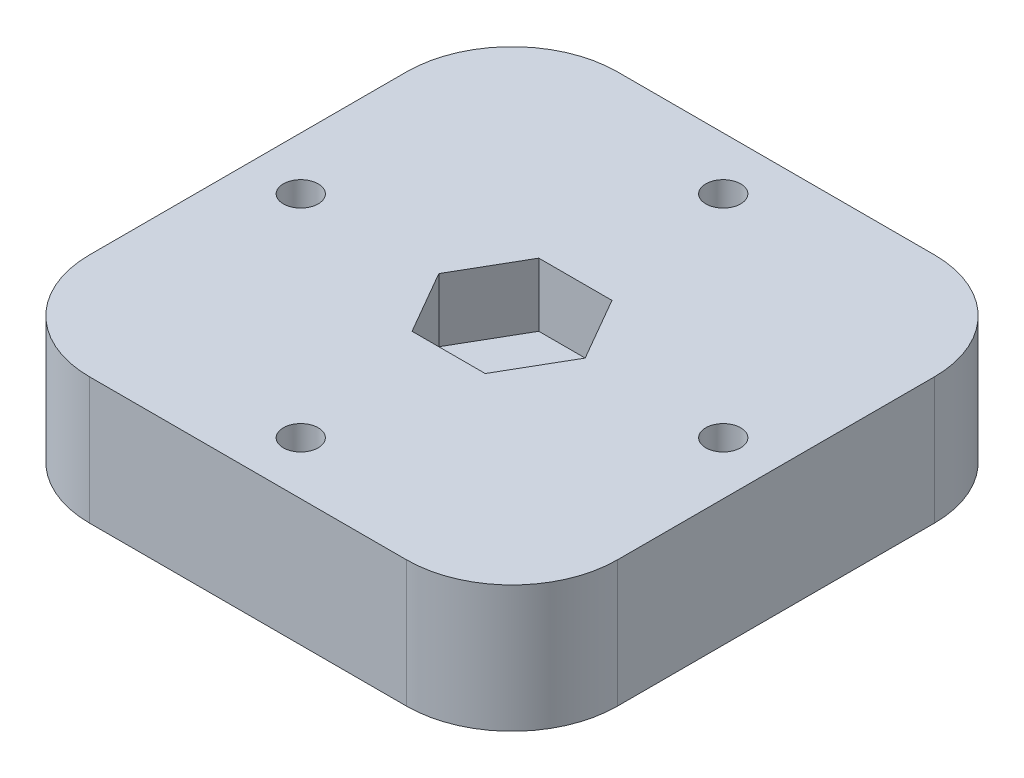
SolidWorks part; units mm, degrees
ref_plane "Front Plane" through (0, 0, 0) normal (0, 0, 1) x (1, 0, 0)
ref_plane "Top Plane" through (0, 0, 0) normal (0, 1, 0) x (1, 0, 0)
ref_plane "Right Plane" through (0, 0, 0) normal (1, 0, 0) x (0, 0, -1)
sketch "Sketch1" plane through (0, 0, 0) normal (0, 1, 0) x (1, 0, 0)
  line L1 (-25, 25) -> (25, 25)
  line L2 (-25, 25) -> (-25, -25)
  line L3 (-25, -25) -> (25, -25)
  line L4 (25, 25) -> (25, -25)
  line L5 (-25, 25) -> (25, -25) construction
  line L6 (-25, -25) -> (25, 25) construction
  point P0 (0, 0)
  dimension "D1" = 50
  dimension "D2" = 50
extrude "Boss-Extrude1" add sketch "Sketch1" along normal blind 12
sketch "Sketch2" plane through (0, 12, 0) normal (0, 1, 0) x (1, 0, 0)
  line L1 (6.9282, 0) -> (3.4641, 6)
  line L2 (3.4641, 6) -> (-3.4641, 6)
  line L3 (-3.4641, 6) -> (-6.9282, 0)
  line L4 (-6.9282, 0) -> (-3.4641, -6)
  line L5 (-3.4641, -6) -> (3.4641, -6)
  line L6 (3.4641, -6) -> (6.9282, 0)
  circle A0 centre (0, 0) radius 6 construction
  dimension "D1" = 12
extrude "Cut-Extrude1" cut sketch "Sketch2" against normal blind 6
sketch "Sketch4" plane through (0, 12, 0) normal (0, 1, 0) x (1, 0, 0)
  line L0 (0, 0) -> (19.863, 0) construction
  line L1 (0, 0) -> (0, 8.4621) construction
  circle A0 centre (0, 20) radius 1.65
  circle A1 centre (20, 0) radius 1.65
  circle A2 centre (-20, 0) radius 1.65
  circle A3 centre (0, -20) radius 1.65
  dimension "D1" = 3.3
  dimension "D3" = 3.3
  dimension "D2" = 20
  dimension "D4" = 20
extrude "Cut-Extrude2" cut sketch "Sketch4" against normal blind 25
fillet "Fillet1" radius 10 4 edges at (25, 6, -25) (25, 6, 25) (-25, 6, 25) (-25, 6, -25)
sketch "Sketch5" plane through (0, 0, 0) normal (0, 1, 0) x (1, 0, 0)
  circle A0 centre (0, 0) radius 2
  dimension "D1" = 4
extrude "Cut-Extrude4" cut sketch "Sketch5" along normal blind 10
